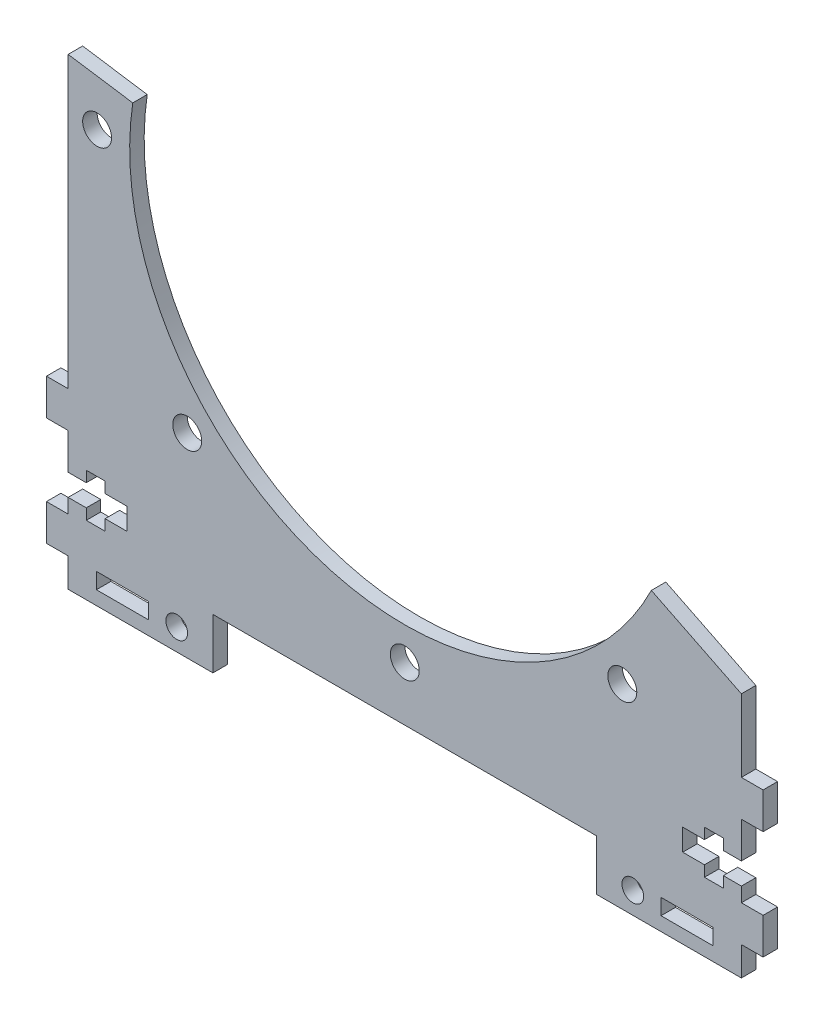
SolidWorks part; units mm, degrees
ref_plane "前视基准面" through (0, 0, 0) normal (0, 0, 1) x (1, 0, 0)
ref_plane "上视基准面" through (0, 0, 0) normal (0, 1, 0) x (1, 0, 0)
ref_plane "右视基准面" through (0, 0, 0) normal (1, 0, 0) x (0, 0, -1)
sketch "草图3" plane through (0, 0, 0) normal (0, 0, 1) x (1, 0, 0)
  line L0 (-42.5, -1.9902) -> (-42.5, -2.0902) construction
  line L2 (-46.5, -1.9902) -> (-46.5, 0.0098) construction
  line L4 (46.5, -1.9902) -> (46.5, 0.0098) construction
  line L5 (-42.5, 0.0098) -> (-35.5, 0.0098) construction
  line L6 (-42.5, 0.0098) -> (-42.5, -1.9902) construction
  line L7 (-42.5, -1.9902) -> (-35.5, -1.9902) construction
  line L8 (-35.5, 0.0098) -> (-35.5, -1.9902) construction
  line L9 (-42.5, -2.0902) -> (-42.6, -2.0902) construction
  line L10 (0, -1.9902) -> (0, 3.216) construction
  line L11 (35.5, 0.0098) -> (42.5, 0.0098) construction
  line L12 (35.5, 0.0098) -> (35.5, -1.9902) construction
  line L13 (35.5, -1.9902) -> (42.5, -1.9902) construction
  line L14 (42.5, 0.0098) -> (42.5, -1.9902) construction
  line L19 (-42.6, -2.0902) -> (-35.4, -2.0902)
  line L20 (-42.6, -2.0902) -> (-42.6, 0.1098)
  line L21 (-42.6, 0.1098) -> (-35.4, 0.1098)
  line L22 (-35.4, -2.0902) -> (-35.4, 0.1098)
  line L23 (35.4, -2.0902) -> (35.4, 0.1098)
  line L24 (42.6, -2.0902) -> (35.4, -2.0902)
  line L25 (42.6, -2.0902) -> (42.6, 0.1098)
  line L26 (42.6, 0.1098) -> (35.4, 0.1098)
  line L27 (-46.5, 0.0098) -> (-46.5, -3.9902)
  line L28 (-46.5, -3.9902) -> (-26.5, -3.9902)
  line L29 (-26.5, -3.9902) -> (-26.5, 3.0098)
  line L30 (46.5, 0.0098) -> (46.5, -3.9902)
  line L31 (46.5, -3.9902) -> (26.5, -3.9902)
  line L32 (26.5, -3.9902) -> (26.5, 3.0098)
  line L33 (-26.5, 3.0098) -> (26.5, 3.0098)
  line L37 (46.5, 30.0098) -> (34.0612, 36.1623)
  line L38 (-46.5, 60.0098) -> (-37.5766, 58.6665)
  line L39 (-46.5, 0.0098) -> (-49.5, 0.0098)
  line L40 (-49.5, 0.0098) -> (-49.5, 5.0098)
  line L41 (-49.5, 5.0098) -> (-46.5, 5.0098)
  line L42 (-44, 7.0098) -> (-44, 5.5098)
  line L43 (-44, 10.0098) -> (-44, 11.5098)
  line L44 (-46.5, 10.0098) -> (-44, 10.0098)
  line L45 (-44, 5.5098) -> (-41.4, 5.5098)
  line L46 (-41.4, 5.5098) -> (-41.4, 7.0098)
  line L47 (-41.4, 7.0098) -> (-38.4, 7.0098)
  line L48 (-38.4, 10.0098) -> (-38.4, 7.0098)
  line L49 (-41.4, 10.0098) -> (-38.4, 10.0098)
  line L50 (-41.4, 11.5098) -> (-41.4, 10.0098)
  line L51 (-44, 11.5098) -> (-41.4, 11.5098)
  line L52 (-44, 7.0098) -> (-46.5, 7.0098)
  line L53 (-46.5, 5.0098) -> (-46.5, 7.0098)
  line L54 (-46.5, 10.0098) -> (-46.5, 15.0098)
  line L55 (-46.5, 15.0098) -> (-49.5, 15.0098)
  line L56 (-49.5, 15.0098) -> (-49.5, 20.0098)
  line L57 (-49.5, 20.0098) -> (-46.5, 20.0098)
  line L58 (-46.5, 20.0098) -> (-46.5, 60.0098)
  line L59 (49.5, 20.0098) -> (46.5, 20.0098)
  line L60 (49.5, 15.0098) -> (49.5, 20.0098)
  line L61 (46.5, 15.0098) -> (49.5, 15.0098)
  line L62 (46.5, 10.0098) -> (46.5, 15.0098)
  line L63 (46.5, 5.0098) -> (46.5, 7.0098)
  line L64 (44, 7.0098) -> (46.5, 7.0098)
  line L65 (44, 11.5098) -> (41.4, 11.5098)
  line L66 (41.4, 11.5098) -> (41.4, 10.0098)
  line L67 (41.4, 10.0098) -> (38.4, 10.0098)
  line L68 (38.4, 10.0098) -> (38.4, 7.0098)
  line L69 (41.4, 7.0098) -> (38.4, 7.0098)
  line L70 (41.4, 5.5098) -> (41.4, 7.0098)
  line L71 (44, 5.5098) -> (41.4, 5.5098)
  line L72 (46.5, 10.0098) -> (44, 10.0098)
  line L73 (44, 10.0098) -> (44, 11.5098)
  line L74 (44, 7.0098) -> (44, 5.5098)
  line L75 (49.5, 5.0098) -> (46.5, 5.0098)
  line L76 (46.5, 0.0098) -> (49.5, 0.0098)
  line L77 (49.5, 0.0098) -> (49.5, 5.0098)
  line L78 (46.5, 20.0098) -> (46.5, 30.0098)
  circle A0 centre (-31.5, -0.9902) radius 1.5
  circle A1 centre (31.5, -0.9902) radius 1.5
  circle A4 centre (0, 10.5098) radius 2
  circle A5 centre (-30.052, 22.9577) radius 2
  circle A6 centre (-42.5, 53.0098) radius 2
  circle A11 centre (30.052, 22.9577) radius 2
  arc A12 (-37.5766, 58.6665) -> (34.0612, 36.1623) centre (0, 53.0098) ccw
  circle A13 centre (42.5, 53.0098) radius 2 [skipped]
  circle A14 centre (30.052, 83.0618) radius 2 [skipped]
  circle A15 centre (-30.052, 83.0618) radius 2 [skipped]
  circle A16 centre (0, 95.5098) radius 2 [skipped]
  dimension "D1" = 8
extrude "凸台-拉伸1" add sketch "草图3" along normal blind 2
sketch "草图4" plane through (46.5, 0, 0) normal (1, 0, 0) x (0, 0, -1)
  line L0 (-2, 10.0098) -> (0, 7.0098)
  circle A0 centre (-1, 8.5098) radius 1.5
sketch "草图5" plane through (-46.5, 0, 0) normal (-1, 0, 0) x (0, 0, 1)
  line L0 (0, 10.0098) -> (2, 7.0098)
  circle A0 centre (1, 8.5098) radius 1.5
